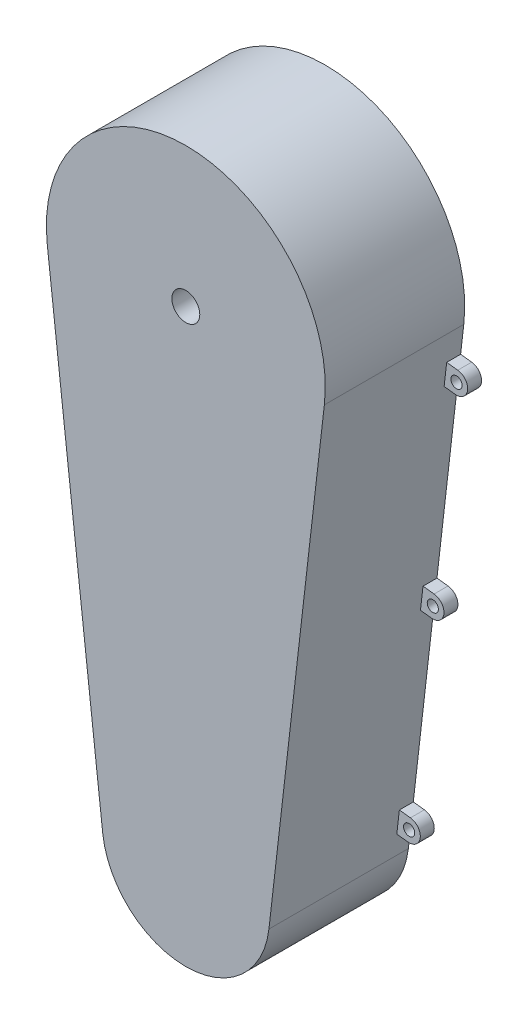
SolidWorks part; units mm, degrees
ref_plane "Front Plane" through (0, 0, 0) normal (1, 0, 0) x (0, 1, 0)
ref_plane "Top Plane" through (0, 0, 0) normal (0, 0, 1) x (0, 1, 0)
ref_plane "Right Plane" through (0, 0, 0) normal (0, 1, 0) x (-1, 0, 0)
sketch "Sketch1" plane through (0, 0, 0) normal (0, 0, 1) x (0, 1, 0)
  line L0 (-356.8571, 59.6069) -> (-11.4286, 99.3448)
  line L1 (-356.8571, -59.6069) -> (-11.4286, -99.3448)
  arc A0 (-11.4286, -99.3448) -> (-11.4286, 99.3448) centre (0, 0) ccw
  arc A1 (-356.8571, 59.6069) -> (-356.8571, -59.6069) centre (-350, 0) ccw
  dimension "D1" = 200
  dimension "D2" = 120
  dimension "D3" = 350
extrude "Boss-Extrude1" add sketch "Sketch1" along normal blind 100
shell "Shell1" thickness 20
sketch "Sketch7" plane through (0, 0, 80) normal (0, 0, -1) x (1, 0, 0)
  circle A0 centre (0, 0) radius 10
  dimension "D1" = 20
extrude "Cut-Extrude2" cut sketch "Sketch7" against normal blind 39
sketch "Sketch8" plane through (0, 0, 0) normal (0, 0, 1) x (0, 1, 0)
  line L0 (-410, 0) -> (100, 0) construction
  line L1 (-11.4286, 99.3448) -> (-356.8571, 59.6069) construction
  line L2 (-342.9476, 69.2598) -> (-342.0333, 61.3122)
  line L3 (-327.0524, 71.0884) -> (-326.1381, 63.1408)
  line L4 (-342.0333, 61.3122) -> (-326.1381, 63.1408)
  line L5 (-179.5524, 88.0567) -> (-178.6381, 80.1091)
  line L6 (-194.5333, 78.2805) -> (-178.6381, 80.1091)
  line L7 (-195.4476, 86.2281) -> (-194.5333, 78.2805)
  line L8 (-32.0524, 105.025) -> (-31.1381, 97.0774)
  line L9 (-47.0333, 95.2488) -> (-31.1381, 97.0774)
  line L10 (-47.9476, 103.1964) -> (-47.0333, 95.2488)
  line L11 (-47.9476, -103.1964) -> (-47.0333, -95.2488)
  line L12 (-47.0333, -95.2488) -> (-31.1381, -97.0774)
  line L13 (-32.0524, -105.025) -> (-31.1381, -97.0774)
  line L14 (-195.4476, -86.2281) -> (-194.5333, -78.2805)
  line L15 (-194.5333, -78.2805) -> (-178.6381, -80.1091)
  line L16 (-179.5524, -88.0567) -> (-178.6381, -80.1091)
  line L17 (-342.0333, -61.3122) -> (-326.1381, -63.1408)
  line L18 (-327.0524, -71.0884) -> (-326.1381, -63.1408)
  line L19 (-342.9476, -69.2598) -> (-342.0333, -61.3122)
  arc A0 (-356.8571, 59.6069) -> (-356.8571, -59.6069) centre (-350, 0) ccw construction
  arc A1 (-11.4286, -99.3448) -> (-11.4286, 99.3448) centre (0, 0) ccw construction
  arc A2 (-327.0524, 71.0884) -> (-342.9476, 69.2598) centre (-335, 70.1741) ccw
  circle A3 centre (-335, 70.1741) radius 4
  arc A4 (-179.5524, 88.0567) -> (-195.4476, 86.2281) centre (-187.5, 87.1424) ccw
  circle A5 centre (-187.5, 87.1424) radius 4
  arc A6 (-32.0524, 105.025) -> (-47.9476, 103.1964) centre (-40, 104.1107) ccw
  circle A7 centre (-40, 104.1107) radius 4
  circle A8 centre (-40, -104.1107) radius 4
  arc A9 (-32.0524, -105.025) -> (-47.9476, -103.1964) centre (-40, -104.1107) cw
  circle A10 centre (-187.5, -87.1424) radius 4
  arc A11 (-179.5524, -88.0567) -> (-195.4476, -86.2281) centre (-187.5, -87.1424) cw
  circle A12 centre (-335, -70.1741) radius 4
  arc A13 (-327.0524, -71.0884) -> (-342.9476, -69.2598) centre (-335, -70.1741) cw
  point P9 (0, 0)
  dimension "D1" = 16
  dimension "D2" = 8
  dimension "D3" = 75
  dimension "D5" = 370
  dimension "D4" = 3
extrude "Boss-Extrude2" add sketch "Sketch8" along normal blind 10
sketch "Sketch9" plane through (0, 0, 0) normal (0, 1, 0) x (-1, 0, 0)
  line L0 (0, 0) -> (-8, 0)
  line L1 (-100, 0) -> (100, 0) construction
  line L2 (-8, 0) -> (-8, 10)
  line L3 (8, 10) -> (8, 0)
  line L4 (0, 0) -> (8, 0)
  arc A0 (-8, 10) -> (8, 10) centre (0, 10) cw
  dimension "D2" = 10
  dimension "D1" = 8
extrude "Cut-Extrude3" cut sketch "Sketch9" against normal blind 423
